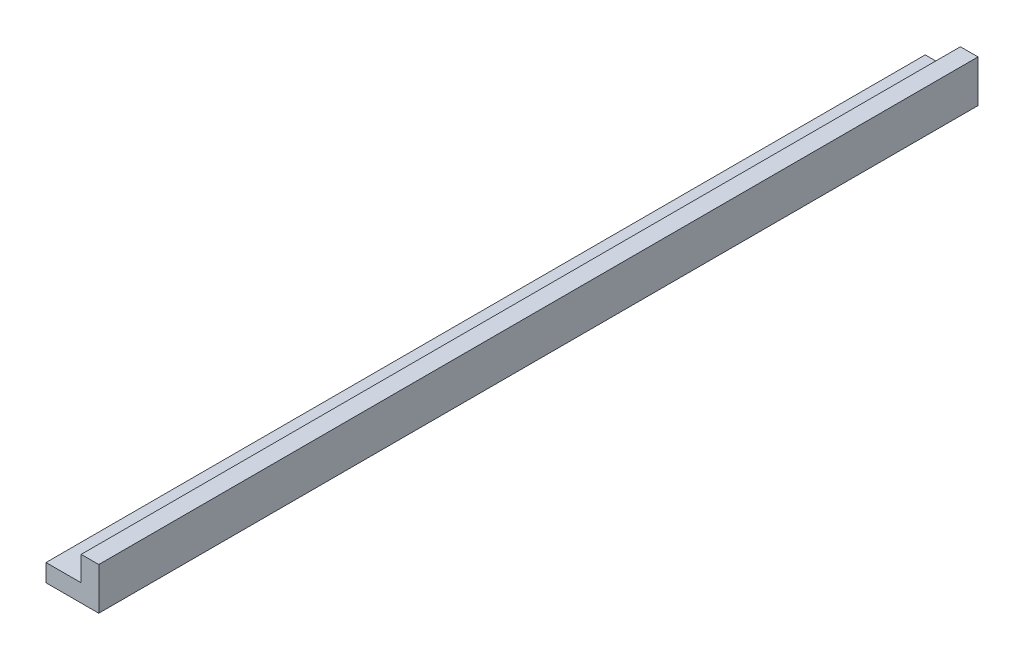
SolidWorks part; units mm, degrees
ref_plane "前视基准面" through (0, 0, 0) normal (0, 0, 1) x (1, 0, 0)
ref_plane "上视基准面" through (0, 0, 0) normal (0, 1, 0) x (1, 0, 0)
ref_plane "右视基准面" through (0, 0, 0) normal (1, 0, 0) x (0, 0, -1)
other "Configuration Table"
sketch "草图1" plane through (0, 0, 0) normal (0, 1, 0) x (1, 0, 0)
  line L1 (-7.5, 125) -> (7.5, 125)
  line L2 (-7.5, 125) -> (-7.5, -125)
  line L3 (-7.5, -125) -> (7.5, -125)
  line L4 (7.5, 125) -> (7.5, -125)
  line L5 (-7.5, 125) -> (7.5, -125) construction
  line L6 (-7.5, -125) -> (7.5, 125) construction
  point P0 (0, 0)
  dimension "D1" = 250
  dimension "D2" = 15
extrude "凸台-拉伸1" add sketch "草图1" along normal blind 5
sketch "草图2" plane through (7.5, 0, 0) normal (1, 0, 0) x (0, 0, -1)
  line L0 (125, 5) -> (125, 0) construction
  line L1 (-125, 0) -> (125, 0)
  line L2 (-125, 0) -> (-125, 12)
  line L3 (-125, 12) -> (125, 12)
  line L4 (125, 0) -> (125, 12)
  dimension "D1" = 0
  dimension "D2" = 12
extrude "凸台-拉伸2" add sketch "草图2" against normal blind 5
sketch "草图3" plane through (0, 5, 0) normal (0, 1, 0) x (1, 0, 0)
  line L0 (-7.5, 125) -> (-7.5, -125) construction
  circle A0 centre (-2.5, 100) radius 1.75
  circle A1 centre (-2.5, 0) radius 1.75
  circle A2 centre (-2.5, -100) radius 1.75
  dimension "D1" = 3.5
  dimension "D2" = 3.5
  dimension "D3" = 3.5
  dimension "D4" = 0
  dimension "D5" = 5
  dimension "D6" = 5
  dimension "D7" = 5
  dimension "D8" = 100
  dimension "D9" = 100
extrude "切除-拉伸1" cut sketch "草图3" against normal blind 5
